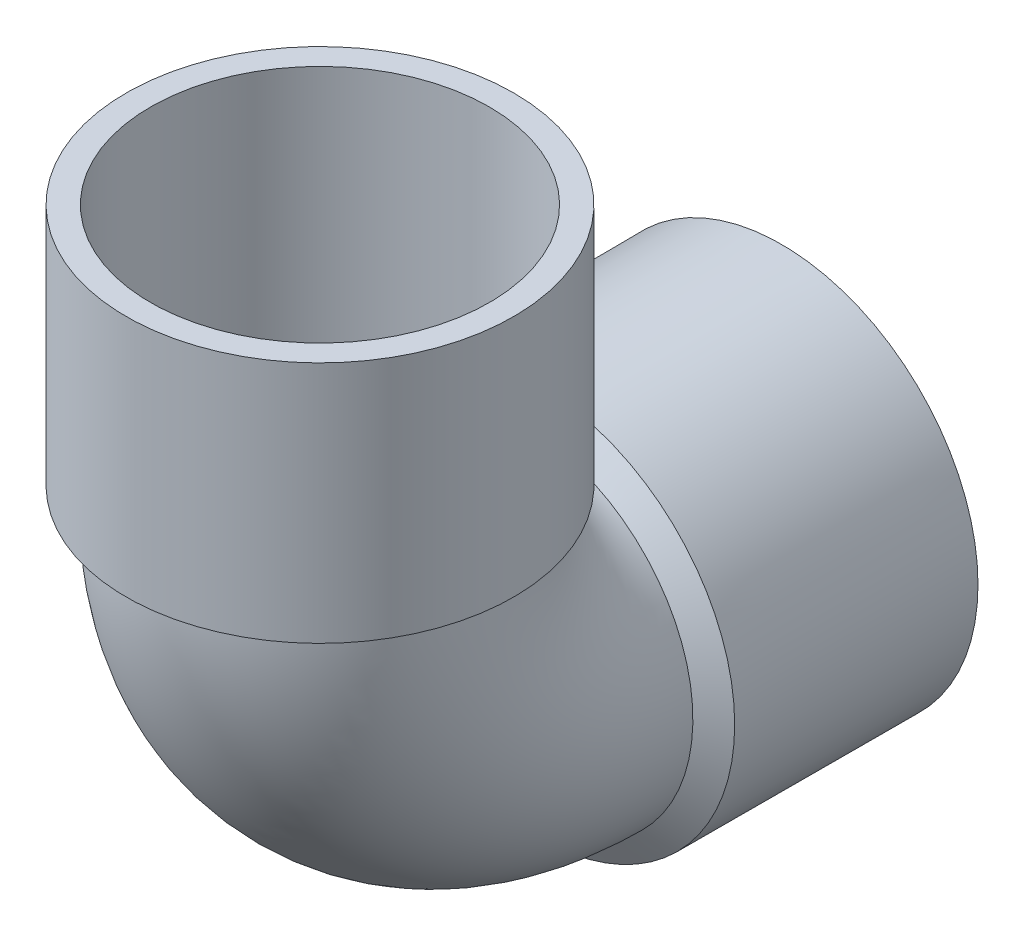
SolidWorks part; units mm, degrees
ref_plane "Front Plane" through (0, 0, 0) normal (0, 0, 1) x (1, 0, 0)
ref_plane "Top Plane" through (0, 0, 0) normal (0, 1, 0) x (1, 0, 0)
ref_plane "Right Plane" through (0, 0, 0) normal (1, 0, 0) x (0, 0, -1)
sketch "Sketch1" plane through (0, 0, 0) normal (0, 1, 0) x (1, 0, 0)
  line L0 (-39.1487, 25) -> (49.6068, 25) construction
  circle A0 centre (0, 0) radius 21.055
  circle A1 centre (0, 0) radius 18.055
  dimension "D1" = 42.11
  dimension "D2" = 3
  dimension "D3" = 25
sketch "Sketch3" plane through (0, 0, 0) normal (0, 1, 0) x (1, 0, 0)
  line L0 (0, -21.055) -> (0, 21.055) construction
  line L1 (0, 21.055) -> (0, 63.165) construction
  line L2 (0, 63.165) -> (39.5529, 63.165) construction
  line L3 (16.9826, 21.055) -> (0, 42.11) construction
  line L4 (54.7797, 31.5825) -> (-37.797, 31.5825) construction
  circle A0 centre (0, 0) radius 21.055 construction
  point P13 (8.4913, 31.5825)
revolve "Revolve1" add sketch "Sketch1" angle 90 about L0
sketch "Sketch14" plane through (0, 0, 0) normal (1, 0, 0) x (0, 0, -1)
  line L0 (-20.9221, 0) -> (-17.9221, 0)
  line L1 (-20.9221, 0) -> (-23.9258, 2)
  line L2 (-17.9221, 0) -> (-20.9258, 2)
  line L3 (-23.9258, 2) -> (-20.9258, 2)
  line L4 (-21.055, 0) -> (21.055, 0) construction
  line L5 (0, 0) -> (0, 19.4811) construction
  line L6 (-23.9258, 2) -> (-20.9258, 2)
  line L7 (-23.9258, 2) -> (-23.9258, 32)
  line L8 (-23.9258, 32) -> (-20.9258, 32)
  line L9 (-20.9258, 2) -> (-20.9258, 32)
  dimension "D1" = 3
  dimension "D2" = 2
  dimension "D3" = 30
revolve "Revolve3" add sketch "Sketch14" angle 360 about L5
sketch "Sketch20" plane through (0, 0, 0) normal (1, 0, 0) x (0, 0, -1)
  line L0 (25, -46.055) -> (25, -43.055)
  line L1 (25, -46.055) -> (27, -49.2174)
  line L2 (25, -43.055) -> (27, -46.2174)
  line L3 (27, -49.2174) -> (27, -46.2174)
  line L4 (25, -46.055) -> (25, -3.945) construction
  line L5 (27, -49.2174) -> (27, -46.2174)
  line L6 (27, -49.2174) -> (57, -49.2653)
  line L7 (27, -46.2174) -> (57, -46.2653)
  line L8 (57, -49.2653) -> (57, -46.2653)
  line L9 (25, -25) -> (59.7168, -25) construction
  line L10 (25, -43.055) -> (25, -6.945) construction
  dimension "D1" = 2
  dimension "D2" = 3
  dimension "D3" = 30
revolve "Revolve4" add sketch "Sketch20" angle 360 about L9
scale "Scale1" scale about centroid uniform scaling yes scale factor 0.760151
